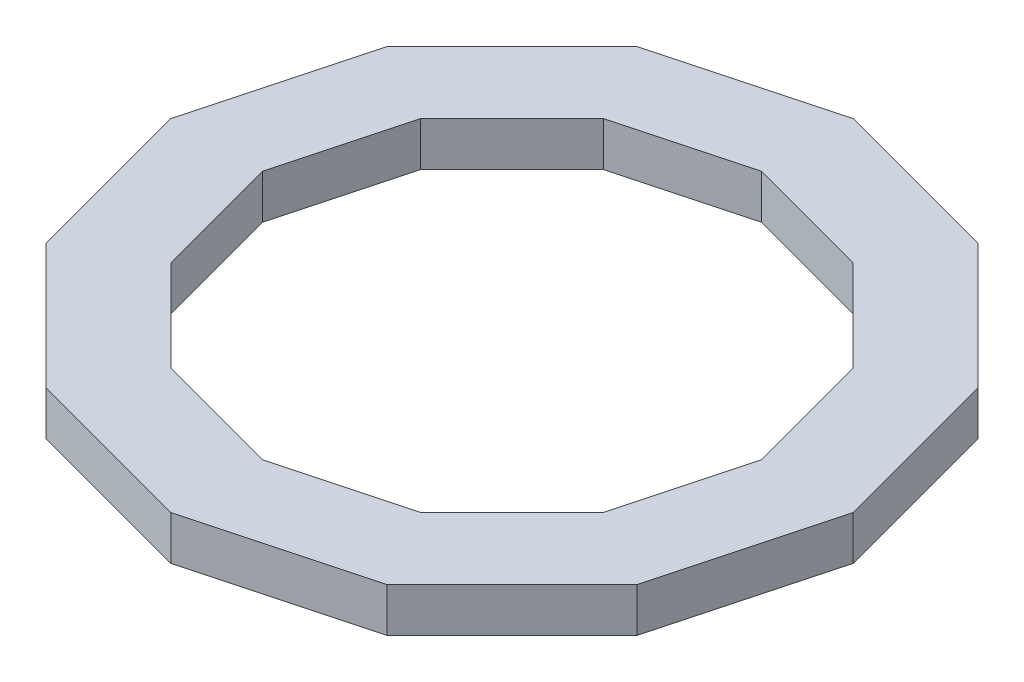
SolidWorks part; units mm, degrees
ref_plane "Front Plane" through (0, 0, 0) normal (0, 0, 1) x (1, 0, 0)
ref_plane "Top Plane" through (0, 0, 0) normal (0, 1, 0) x (1, 0, 0)
ref_plane "Right Plane" through (0, 0, 0) normal (1, 0, 0) x (0, 0, -1)
sketch "Sketch2" plane through (0, 0, 0) normal (0, 1, 0) x (1, 0, 0)
  line L0 (0, 0) -> (-107.7631, 0) construction
  line L1 (-147.2071, 0) -> (-127.4851, -73.6035)
  line L2 (-127.4851, -73.6035) -> (-73.6035, -127.4851)
  line L3 (-73.6035, -127.4851) -> (0, -147.2071)
  line L4 (0, -147.2071) -> (73.6035, -127.4851)
  line L5 (73.6035, -127.4851) -> (127.4851, -73.6035)
  line L6 (127.4851, -73.6035) -> (147.2071, 0)
  line L7 (147.2071, 0) -> (127.4851, 73.6035)
  line L8 (127.4851, 73.6035) -> (73.6035, 127.4851)
  line L9 (73.6035, 127.4851) -> (0, 147.2071)
  line L10 (0, 147.2071) -> (-73.6035, 127.4851)
  line L11 (-73.6035, 127.4851) -> (-127.4851, 73.6035)
  line L12 (-127.4851, 73.6035) -> (-147.2071, 0)
  line L13 (-107.7631, 0) -> (-93.3256, -53.8815)
  line L14 (-93.3256, -53.8815) -> (-53.8815, -93.3256)
  line L15 (-53.8815, -93.3256) -> (0, -107.7631)
  line L16 (0, -107.7631) -> (53.8815, -93.3256)
  line L17 (53.8815, -93.3256) -> (93.3256, -53.8815)
  line L18 (93.3256, -53.8815) -> (107.7631, 0)
  line L19 (107.7631, 0) -> (93.3256, 53.8815)
  line L20 (93.3256, 53.8815) -> (53.8815, 93.3256)
  line L21 (53.8815, 93.3256) -> (0, 107.7631)
  line L22 (0, 107.7631) -> (-53.8815, 93.3256)
  line L23 (-53.8815, 93.3256) -> (-93.3256, 53.8815)
  line L24 (-93.3256, 53.8815) -> (-107.7631, 0)
  line L25 (-147.2071, 0) -> (-107.7631, 0) construction
  circle A0 centre (0, 0) radius 142.1911 construction
  circle A1 centre (0, 0) radius 104.0911 construction
  dimension "D1" = 76.2
  dimension "D2" = 38.1
extrude "Boss-Extrude2" add sketch "Sketch2" along normal blind 19.05
